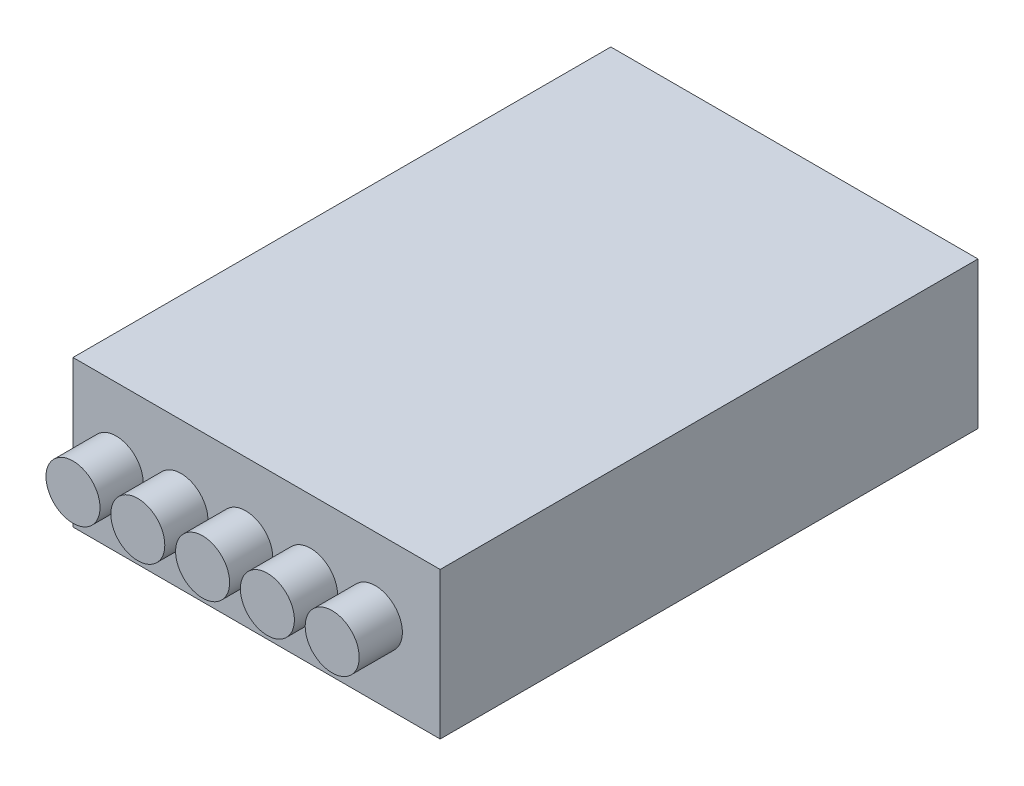
SolidWorks part; units mm, degrees
ref_plane "Front Plane" through (0, 0, 0) normal (0, 0, 1) x (1, 0, 0)
ref_plane "Top Plane" through (0, 0, 0) normal (0, 1, 0) x (1, 0, 0)
ref_plane "Right Plane" through (0, 0, 0) normal (1, 0, 0) x (0, 0, -1)
other "Center of Mass"
sketch "Sketch1" plane through (0, 0, 0) normal (0, 1, 0) x (1, 0, 0)
  line L1 (-85, 124.5) -> (85, 124.5)
  line L2 (-85, 124.5) -> (-85, -124.5)
  line L3 (-85, -124.5) -> (85, -124.5)
  line L4 (85, 124.5) -> (85, -124.5)
  line L5 (-85, 124.5) -> (85, -124.5) construction
  line L6 (-85, -124.5) -> (85, 124.5) construction
  point P0 (0, 0)
  dimension "D1" = 249
  dimension "D2" = 170
extrude "Boss-Extrude1" add sketch "Sketch1" along normal blind 68
sketch "Sketch2" plane through (0, 0, 124.5) normal (0, 0, 1) x (1, 0, 0)
  line L0 (-85, 68) -> (-85, 0) construction
  line L1 (-65, 34) -> (-35, 34) construction
  circle A0 centre (-65, 34) radius 12.5
  circle A1 centre (-35, 34) radius 12.5
  circle A2 centre (-5, 34) radius 12.5
  circle A3 centre (25, 34) radius 12.5
  circle A4 centre (55, 34) radius 12.5
  point P5 (-85, 34)
  dimension "D1" = 25
  dimension "D2" = 20
  dimension "D4" = 30
  dimension "D3" = 5
extrude "Boss-Extrude2" add sketch "Sketch2" along normal blind 20
